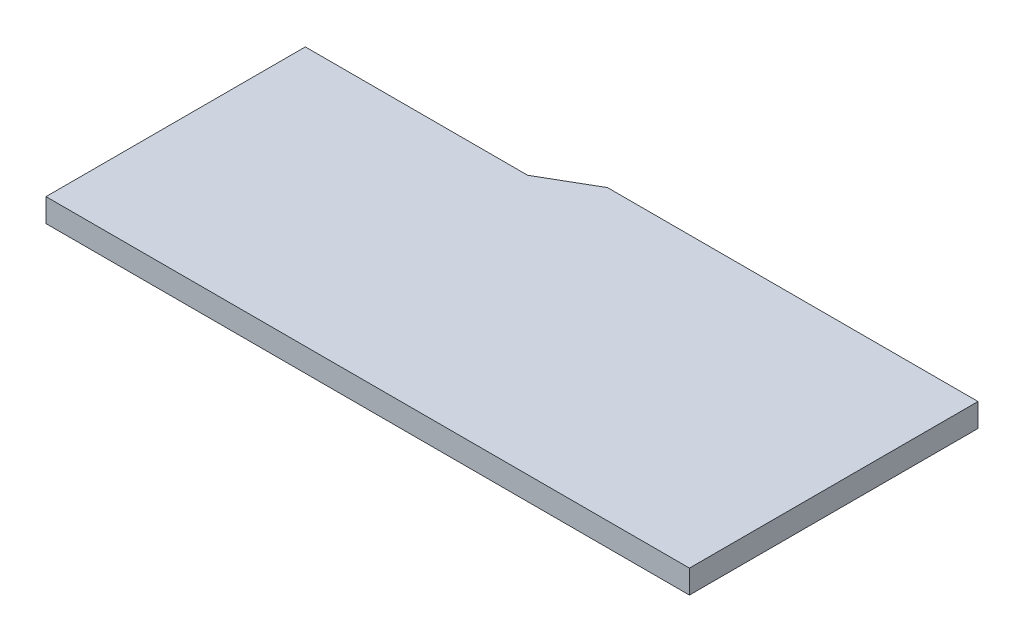
SolidWorks part; units mm, degrees
ref_plane "Alzado" through (0, 0, 0) normal (0, 0, 1) x (1, 0, 0)
ref_plane "Planta" through (0, 0, 0) normal (0, 1, 0) x (1, 0, 0)
ref_plane "Vista lateral" through (0, 0, 0) normal (1, 0, 0) x (0, 0, -1)
sketch "Croquis1" plane through (0, 0, 0) normal (0, 1, 0) x (1, 0, 0)
  line L0 (-165, 133) -> (-165, 0)
  line L1 (-165, 0) -> (165, 0)
  line L2 (165, 0) -> (165, 148)
  line L3 (165, 148) -> (-25, 148)
  line L6 (-25, 148) -> (-50.9808, 133)
  line L7 (-50.9808, 133) -> (-165, 133)
  point P8 (0, 0)
  dimension "D1" = 133
  dimension "D2" = 148
  dimension "D3" = 330
  dimension "D4" = 190
  dimension "D5" = 30
extrude "Saliente-Extruir1" add sketch "Croquis1" along normal blind 12
